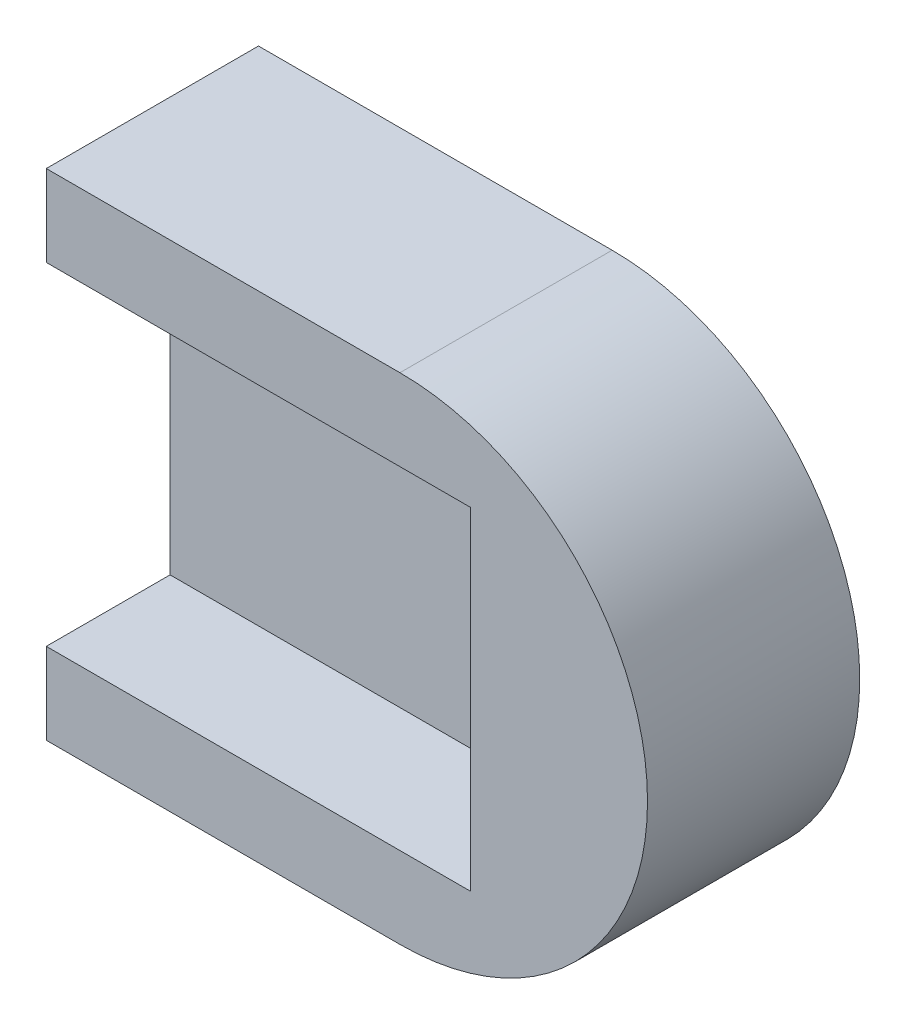
SolidWorks part; units mm, degrees
ref_plane "正面" through (0, 0, 0) normal (0, 0, 1) x (1, 0, 0)
ref_plane "平面" through (0, 0, 0) normal (0, 1, 0) x (1, 0, 0)
ref_plane "右側面" through (0, 0, 0) normal (1, 0, 0) x (0, 0, -1)
sketch "ｽｹｯﾁ1" plane through (0, 0, 0) normal (0, 0, 1) x (1, 0, 0)
  line L0 (50, 0) -> (-50, 0) construction
  line L1 (-50, 70) -> (50, 70)
  line L2 (-50, 70) -> (-50, -70)
  line L3 (-50, -70) -> (50, -70)
  line L4 (50, 70) -> (50, -70) construction
  line L6 (0, 70) -> (0, -70) construction
  arc A0 (50, 70) -> (50, -70) centre (50, 0) cw
  dimension "D1" = 100
  dimension "D2" = 140
extrude "ﾎﾞｽ - 押し出し1" add sketch "ｽｹｯﾁ1" along normal blind 60
sketch "ｽｹｯﾁ2" plane through (0, 0, 60) normal (0, 0, 1) x (1, 0, 0)
  line L0 (-50, 70) -> (-50, -70) construction
  line L1 (-50, 47) -> (70, 47)
  line L2 (-50, 47) -> (-50, -47)
  line L3 (-50, -47) -> (70, -47)
  line L4 (70, 47) -> (70, -47)
  line L5 (120, 0) -> (-50, 0) construction
  arc A0 (50, -70) -> (50, 70) centre (50, 0) ccw construction
  point P12 (0, 0)
  point P13 (-50, 0)
  dimension "D1" = 120
  dimension "D2" = 94
extrude "ｶｯﾄ - 押し出し1" cut sketch "ｽｹｯﾁ2" against normal blind 35
sketch "ｽｹｯﾁ3" plane through (0, 0, 0) normal (0, 0, -1) x (-1, 0, 0)
  line L0 (50, 0) -> (-30, 0) construction
  line L1 (50, 70) -> (50, -70) construction
  circle A0 centre (-30, 0) radius 20
  dimension "D1" = 40
  dimension "D2" = 80
extrude "ｶｯﾄ - 押し出し2" cut sketch "ｽｹｯﾁ3" against normal blind 15
